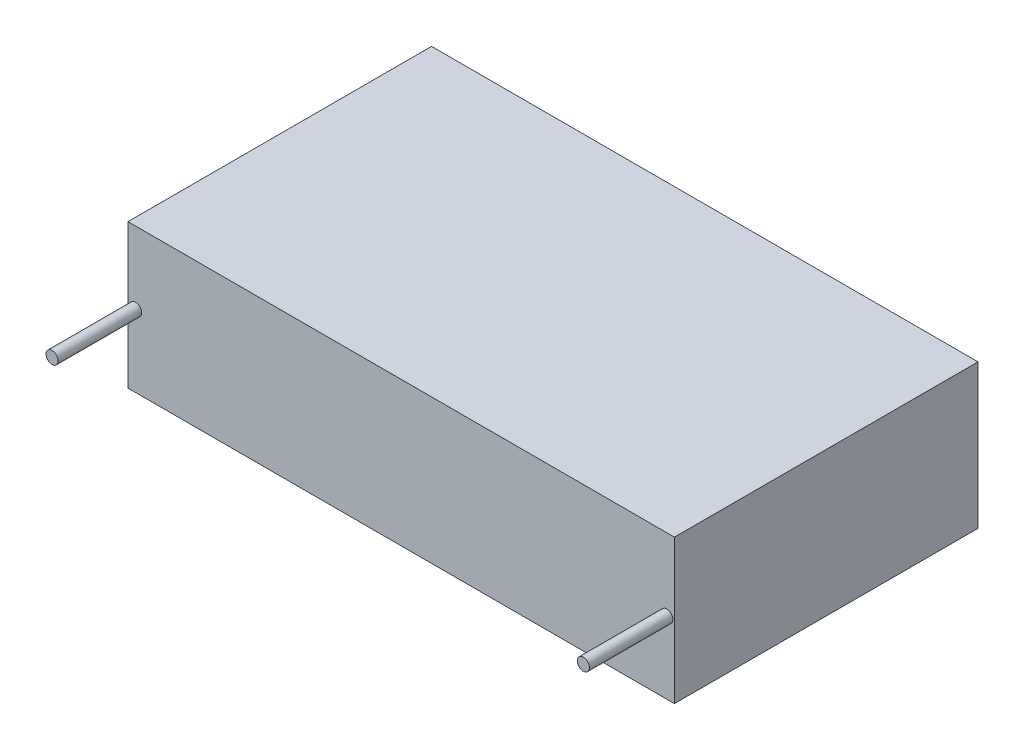
SolidWorks part; units mm, degrees
ref_plane "Спереди" through (0, 0, 0) normal (0, 0, 1) x (1, 0, 0)
ref_plane "Сверху" through (0, 0, 0) normal (0, 1, 0) x (1, 0, 0)
ref_plane "Справа" through (0, 0, 0) normal (1, 0, 0) x (0, 0, -1)
sketch "Эскиз1" plane through (0, 0, 0) normal (0, 0, 1) x (1, 0, 0)
  line L1 (0, 0) -> (36, 0)
  line L2 (0, 0) -> (0, 9.5)
  line L3 (0, 9.5) -> (36, 9.5)
  line L4 (36, 0) -> (36, 9.5)
  dimension "D1" = 9.5
  dimension "D2" = 36
extrude "Вытянуть1" add sketch "Эскиз1" along normal blind 20
sketch "Эскиз2" plane through (0, 0, 20) normal (0, 0, 1) x (1, 0, 0)
  line L0 (-0.6613, 4.75) -> (24.2043, 4.75) construction
  line L1 (0, 0) -> (36, 0) construction
  line L2 (36, 9.5) -> (0, 9.5) construction
  line L3 (18, 10.4113) -> (18, -0.9059) construction
  line L4 (0, 9.5) -> (0, 0) construction
  line L5 (36, 0) -> (36, 9.5) construction
  circle A0 centre (0.5, 4.75) radius 0.4
  circle A1 centre (35.5, 4.75) radius 0.4
  dimension "D1" = 35
  dimension "D2" = 0.8
extrude "Вытянуть2" add sketch "Эскиз2" along normal blind 5.5
